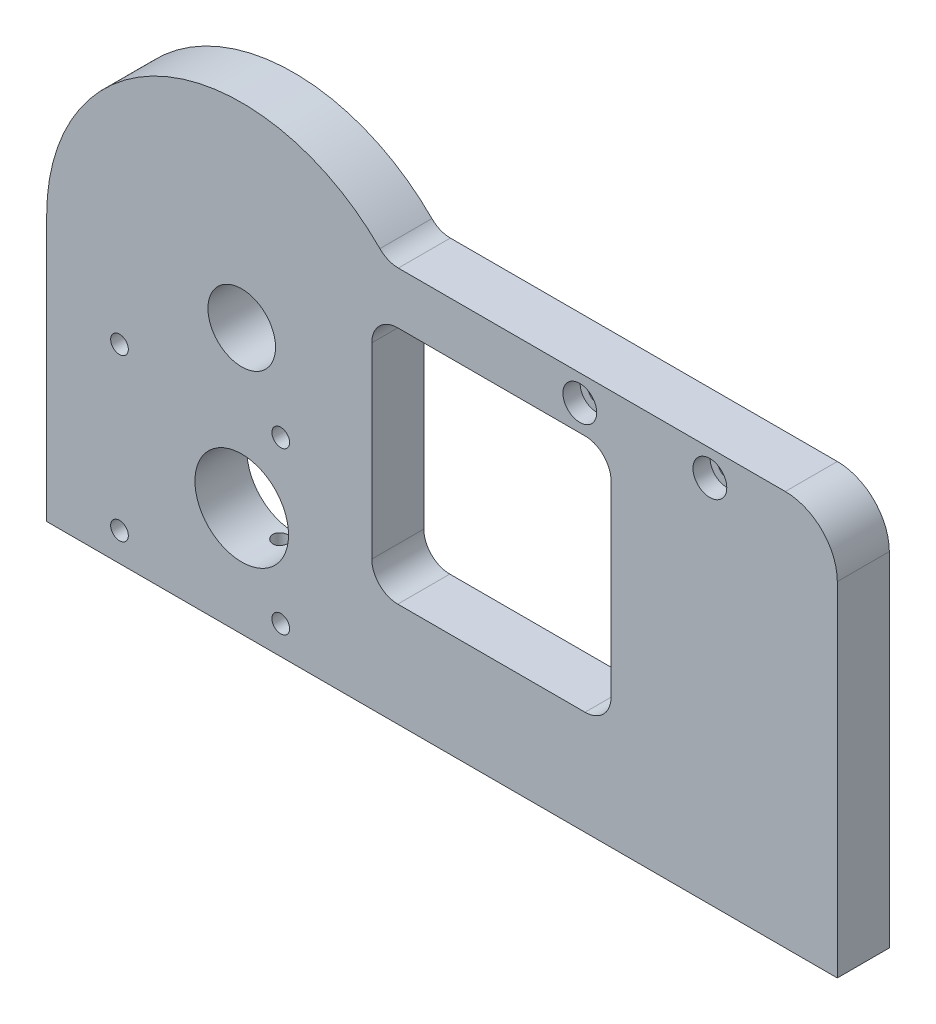
SolidWorks part; units mm, degrees
ref_plane "Front Plane" through (0, 0, 0) normal (0, 0, 1) x (1, 0, 0)
ref_plane "Top Plane" through (0, 0, 0) normal (0, 1, 0) x (1, 0, 0)
ref_plane "Right Plane" through (0, 0, 0) normal (1, 0, 0) x (0, 0, -1)
sketch "Sketch1" plane through (0, 0, 0) normal (0, 0, 1) x (1, 0, 0)
  line L1 (0, 0) -> (152, 0)
  line L2 (0, 0) -> (0, 51)
  line L3 (65.4508, 76) -> (152, 76)
  line L4 (152, 0) -> (152, 76)
  arc A0 (65.4508, 76) -> (0, 51) centre (37.5, 51) ccw
extrude "Boss-Extrude1" add sketch "Sketch1" along normal blind 10
fillet "Fillet1" radius 5 1 edges at (65.4508, 76, 5)
fillet "Fillet2" radius 10 1 edges at (152, 76, 5)
sketch "Sketch2" plane through (0, 0, 10) normal (0, 0, 1) x (1, 0, 0)
  circle A0 centre (37.5, 21) radius 9
extrude "Cut-Extrude1" cut sketch "Sketch2" against normal through all
sketch "Sketch3" plane through (0, 0, 10) normal (0, 0, 1) x (1, 0, 0)
  circle A0 centre (37.5, 51) radius 6.5
extrude "Cut-Extrude2" cut sketch "Sketch3" against normal through all
sketch "Sketch4" plane through (0, 0, 10) normal (0, 0, 1) x (1, 0, 0)
  line L1 (62.5, 20) -> (108.5, 20)
  line L2 (62.5, 20) -> (62.5, 66)
  line L3 (62.5, 66) -> (108.5, 66)
  line L4 (108.5, 20) -> (108.5, 66)
  line L5 (62.5, 20) -> (108.5, 66) construction
  line L6 (62.5, 66) -> (108.5, 20) construction
  point P4 (95.4918, 45.3854)
extrude "Cut-Extrude3" cut sketch "Sketch4" against normal through all
sketch "Sketch5" plane through (0, 0, 0) normal (0, -1, 0) x (1, 0, 0)
  circle A0 centre (37.5, 2.5) radius 1.5
extrude "Cut-Extrude4" cut sketch "Sketch5" against normal up to next
fillet "Fillet3" radius 5 4 edges at (62.5, 20, 5) (108.5, 20, 5) (62.5, 66, 5) (108.5, 66, 5)
sketch "Sketch8" plane through (0, 0, 0) normal (0, 0, 1) x (1, 0, 0)
  point P0 (14, 36.5)
  point P2 (45, 36.5)
  point P4 (45, 5.5)
  point P6 (14, 5.5)
sketch "Sketch6" plane through (0, 0, 0) normal (0, -1, 0) x (-1, 0, 0)
  point P0 (-16, -5)
  point P2 (-56, -5)
  point P4 (-96, -5)
  point P6 (-136, -5)
hole_wizard "M3x0.5 Tapped Hole1" positions "Sketch6" profile "Sketch7" tap size "M3x0.5" standard "JIS"
sketch "Sketch7" plane through (16, 0, 5) normal (1, 0, 0) x (0, 0, -1)
  line L0 (0, 0) -> (0, 9.7811)
  line L1 (0, 9.7811) -> (1.3, 9)
  line L2 (1.3, 9) -> (1.3, 0)
  line L5 (1.3, 0) -> (0, 0)
  line L10 (0, 9.7811) -> (-1.3, 9) construction
  line L11 (0, -6.35) -> (0, 107.95) construction
  dimension "Tap Drill Dia." = 2.6
  dimension "Tap Drill Depth" = 9
  dimension "Drill Angle" = 118
cosmetic thread "Hole Thread1" parameters "D1"=6, "D2"=3
cosmetic thread "Hole Thread2" parameters "D1"=6, "D2"=3
cosmetic thread "Hole Thread3" parameters "D1"=6, "D2"=3
cosmetic thread "Hole Thread4" parameters "D1"=6, "D2"=3
hole_wizard "CBORE for M3 Pan Head Screw1" positions "Sketch8" profile "Sketch9" counterbore size "M3" standard "JIS" end condition through all
sketch "Sketch9" plane through (14, 36.5, 0) normal (1, 0, 0) x (0, 1, 0)
  line L0 (0, 0) -> (0, 10)
  line L1 (0, 10) -> (1.7, 10)
  line L3 (1.7, 10) -> (1.7, 3.3)
  line L4 (1.7, 3.3) -> (3.25, 3.3)
  line L5 (3.25, 3.3) -> (3.25, 0)
  line L7 (3.25, 0) -> (0, 0)
  line L11 (0, -6.35) -> (0, 107.95) construction
  dimension "Thru Hole Dia." = 3.4
  dimension "Thru Hole Depth" = 10
  dimension "C'Bore Dia." = 6.5
  dimension "C'Bore Depth" = 3.3
sketch "Sketch10" plane through (0, 0, 10) normal (0, 0, -1) x (-1, 0, 0)
  point P0 (-127.5, 71)
  point P2 (-102.5, 71)
hole_wizard "CBORE for M3 Pan Head Screw2" positions "Sketch10" profile "Sketch11" counterbore size "M3" standard "JIS" end condition through all
sketch "Sketch11" plane through (127.5, 71, 10) normal (1, 0, 0) x (0, -1, 0)
  line L0 (0, 0) -> (0, 10)
  line L1 (0, 10) -> (1.7, 10)
  line L3 (1.7, 10) -> (1.7, 3.3)
  line L4 (1.7, 3.3) -> (3.25, 3.3)
  line L5 (3.25, 3.3) -> (3.25, 0)
  line L7 (3.25, 0) -> (0, 0)
  line L11 (0, -6.35) -> (0, 107.95) construction
  dimension "Thru Hole Dia." = 3.4
  dimension "Thru Hole Depth" = 10
  dimension "C'Bore Dia." = 6.5
  dimension "C'Bore Depth" = 3.3
